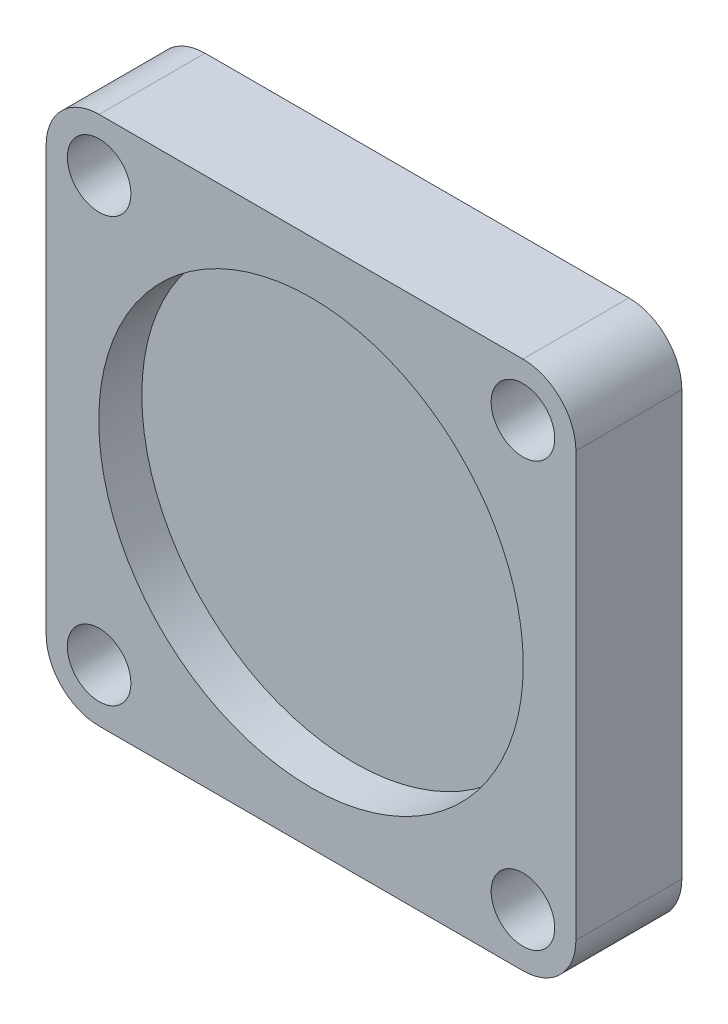
SolidWorks part; units mm, degrees
ref_plane "Plan de face" through (0, 0, 0) normal (0, 0, 1) x (1, 0, 0)
ref_plane "Plan de dessus" through (0, 0, 0) normal (0, 1, 0) x (1, 0, 0)
ref_plane "Plan de droite" through (0, 0, 0) normal (1, 0, 0) x (0, 0, -1)
sketch "Esquisse1" plane through (0, 0, 0) normal (0, 0, 1) x (1, 0, 0)
  line L1 (-10, 12.5) -> (10, 12.5)
  line L2 (-12.5, 10) -> (-12.5, -10)
  line L3 (-10, -12.5) -> (10, -12.5)
  line L4 (12.5, 10) -> (12.5, -10)
  line L5 (-12.5, 12.5) -> (12.5, -12.5) construction
  line L6 (-12.5, -12.5) -> (12.5, 12.5) construction
  arc A0 (10, -12.5) -> (12.5, -10) centre (10, -10) ccw
  arc A1 (10, 12.5) -> (12.5, 10) centre (10, 10) cw
  arc A2 (-12.5, -10) -> (-10, -12.5) centre (-10, -10) ccw
  arc A3 (-10, 12.5) -> (-12.5, 10) centre (-10, 10) ccw
  circle A4 centre (-10, 10) radius 1.5
  circle A5 centre (0, 0) radius 14.1421 construction
  circle A6 centre (10, 10) radius 1.5
  circle A7 centre (10, -10) radius 1.5
  circle A8 centre (-10, -10) radius 1.5
  point P0 (0, 0)
  point P30 (0, 0)
  dimension "D3" = 2.5
  dimension "D4" = 3
  dimension "D1" = 25
  dimension "D2" = 25
  dimension "D5" = 4
extrude "Boss.-Extru.1" add sketch "Esquisse1" along normal blind 5
sketch "Esquisse2" plane through (0, 0, 5) normal (0, 0, 1) x (1, 0, 0)
  circle A0 centre (0, 0) radius 10.015
  dimension "D1" = 20.03
extrude "Enlèv. mat.-Extru.1" cut sketch "Esquisse2" against normal blind 2.03
